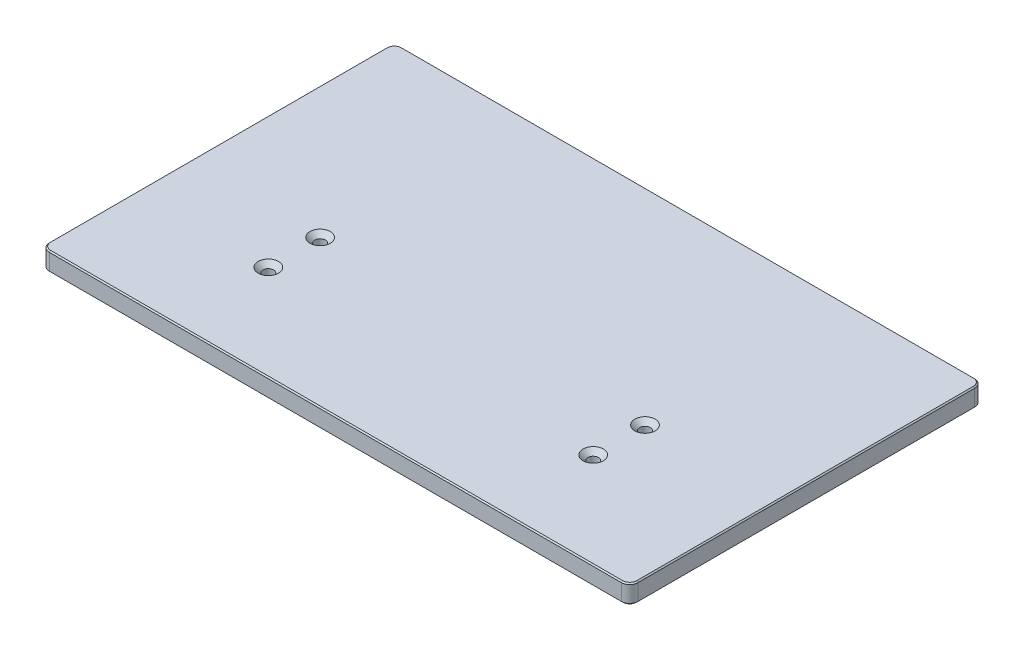
SolidWorks part; units mm, degrees
material "6061-T6 Aluminum"
ref_plane "Front Plane" through (0, 0, 0) normal (0, 0, 1) x (1, 0, 0)
ref_plane "Top Plane" through (0, 0, 0) normal (0, 1, 0) x (1, 0, 0)
ref_plane "Right Plane" through (0, 0, 0) normal (1, 0, 0) x (0, 0, -1)
sketch "Sketch1" plane through (0, 0, 0) normal (0, 1, 0) x (1, 0, 0)
  line L1 (-250, -150) -> (250, -150)
  line L2 (-250, -150) -> (-250, 150)
  line L3 (-250, 150) -> (250, 150)
  line L4 (250, -150) -> (250, 150)
  line L5 (-250, -150) -> (250, 150) construction
  line L6 (-250, 150) -> (250, -150) construction
  point P0 (0, 0)
  dimension "D1" = 500
  dimension "D2" = 300
extrude "Boss-Extrude1" add sketch "Sketch1" along normal blind 15.875
sketch "Sketch6" plane through (0, 0, 0) normal (0, -1, 0) x (1, 0, 0)
  circle A8 centre (138, 69) radius 4.5 construction
  circle A9 centre (138, 25) radius 4.5 construction
  circle A10 centre (-138, 69) radius 4.5 construction
  circle A11 centre (-138, 25) radius 4.5 construction
  circle A12 centre (138, 69) radius 4.5
  circle A13 centre (138, 25) radius 4.5
  circle A14 centre (-138, 69) radius 4.5
  circle A15 centre (-138, 25) radius 4.5
sketch "Sketch7" plane through (0, 15.875, 0) normal (0, 1, 0) x (1, 0, 0)
  line L0 (236, -86.4) -> (236, -142) construction
  line L1 (212.1875, 142) -> (236, 142)
  line L2 (212.1875, 142) -> (212.1875, 86.4)
  line L3 (212.1875, 86.4) -> (236, 86.4)
  line L4 (236, 142) -> (236, 86.4)
  line L5 (212.1875, 142) -> (236, 86.4) construction
  line L6 (212.1875, 86.4) -> (236, 142) construction
  line L7 (236, -142) -> (212.1875, -142) construction
  line L9 (250, -150) -> (250, 150) construction
  line L10 (250, 150) -> (-250, 150) construction
  line L11 (212.1875, -142) -> (212.1875, -86.4) construction
  line L12 (212.1875, -86.4) -> (236, -86.4) construction
  line L13 (-250, -150) -> (250, -150) construction
  point P0 (224.0938, 114.2)
  dimension "D1" = 23.8125
  dimension "D2" = 14
  dimension "D3" = 8
  dimension "D4" = 55.6
  dimension "D5" = 8
sketch "Sketch12" plane through (0, 15.875, 0) normal (0, 1, 0) x (1, 0, 0)
  circle A0 centre (0, 337.3665) radius 4.25 construction
  circle A4 centre (50, 287.3665) radius 4.25 construction
  circle A8 centre (50, 287.3665) radius 4.25
  circle A16 centre (0, 337.3665) radius 4.25
  circle A18 centre (0, 237.3665) radius 4.25 construction
  circle A20 centre (0, 237.3665) radius 4.25
  circle A22 centre (-50, 287.3665) radius 4.25 construction
  circle A24 centre (-50, 287.3665) radius 4.25
sketch "Sketch15" plane through (0, 0, 0) normal (0, -1, 0) x (1, 0, 0)
  circle A0 centre (91.3, -217.9665) radius 4.7625 construction
  circle A1 centre (132.575, -217.9665) radius 4.7625 construction
  circle A2 centre (132.575, -259.2415) radius 4.7625 construction
  circle A3 centre (91.3, -259.2415) radius 4.7625 construction
  circle A4 centre (91.3, -217.9665) radius 4.7625
  circle A5 centre (132.575, -217.9665) radius 4.7625
  circle A6 centre (132.575, -259.2415) radius 4.7625
  circle A7 centre (91.3, -259.2415) radius 4.7625
sketch "Sketch18" plane through (0, 0, 0) normal (0, -1, 0) x (1, 0, 0)
  circle A0 centre (145.2562, 373.8562) radius 3.175 construction
  circle A1 centre (145.2562, 373.8562) radius 3.175
  circle A2 centre (121.4437, 373.8562) radius 3.175 construction
  circle A3 centre (121.4437, 319.8813) radius 3.175 construction
  circle A4 centre (145.2562, 319.8813) radius 3.175 construction
  circle A5 centre (121.4437, 373.8562) radius 3.175
  circle A6 centre (121.4437, 319.8813) radius 3.175
  circle A7 centre (145.2562, 319.8813) radius 3.175
  circle A8 centre (116.6812, -371.4437) radius 3.175 construction
  circle A9 centre (140.4937, -371.4437) radius 3.175 construction
  circle A10 centre (140.4937, -317.4687) radius 3.175 construction
  circle A11 centre (116.6812, -317.4687) radius 3.175 construction
  circle A12 centre (116.6812, -371.4437) radius 3.175
  circle A13 centre (140.4937, -371.4437) radius 3.175
  circle A14 centre (140.4937, -317.4687) radius 3.175
  circle A15 centre (116.6812, -317.4687) radius 3.175
fillet "Fillet1" radius 7 4 edges at (-250, 7.9375, -150) (250, 7.9375, -150) (250, 7.9375, 150) (-250, 7.9375, 150)
chamfer "Chamfer4" distance 1 angle 45 16 edges at (250, 0, 0) (247.9497, 0, -147.9497) (247.9497, 0, 147.9497) (0, 0, -150) (0, 0, 150) (-247.9497, 0, -147.9497) (-247.9497, 0, 147.9497) (-250, 0, 0) (250, 15.875, 0) (247.9497, 15.875, -147.9497) (247.9497, 15.875, 147.9497) (0, 15.875, -150) (0, 15.875, 150) (-247.9497, 15.875, -147.9497) (-247.9497, 15.875, 147.9497) (-250, 15.875, 0)
sketch "Sketch21" plane through (0, 15.875, 0) normal (0, 1, 0) x (1, 0, 0)
  circle A0 centre (138, -69) radius 4.5 construction
  circle A1 centre (138, -25) radius 4.5 construction
  circle A2 centre (138, -69) radius 4.5
  circle A3 centre (138, -25) radius 4.5
hole_wizard "CSK for M8 Flat Head Machine Screw1" positions "Sketch22" profile "Sketch23" countersink size "M8" standard "ANSI Metric" end condition through all
sketch "Sketch22" plane through (0, 15.875, 0) normal (0, 1, 0) x (1, 0, 0)
  point P0 (138, -25)
  point P3 (138, -69)
sketch "Sketch23" plane through (138, 15.875, 25) normal (1, 0, 0) x (0, 0, 1)
  line L0 (0, 0) -> (0, 15.875)
  line L1 (0, 15.875) -> (4.5, 15.875)
  line L2 (4.5, 15.875) -> (4.5, 4.15)
  line L3 (4.5, 4.15) -> (8.65, 0)
  line L5 (8.65, 0) -> (0, 0)
  line L6 (-4.5, 4.15) -> (-8.65, 0) construction
  line L11 (0, -6.35) -> (0, 107.95) construction
  dimension "Thru Hole Dia." = 9
  dimension "Thru Hole Depth" = 15.875
  dimension "Near C'Sink Dia." = 17.3
  dimension "Near C'Sink Angle" = 90
mirror "Mirror3" about plane through (0, 0, 0) normal (1, 0, 0) of "CSK for M8 Flat Head Machine Screw1"
